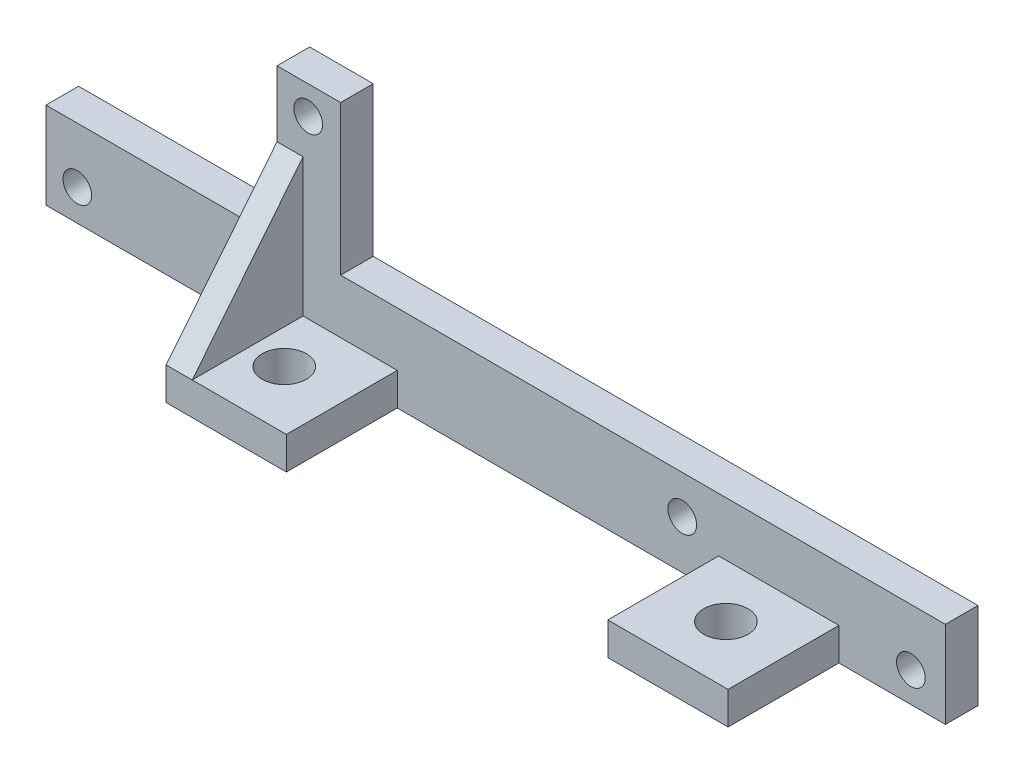
SolidWorks part; units mm, degrees
ref_plane "Front Plane" through (0, 0, 0) normal (0, 0, 1) x (1, 0, 0)
ref_plane "Top Plane" through (0, 0, 0) normal (0, 1, 0) x (1, 0, 0)
ref_plane "Right Plane" through (0, 0, 0) normal (1, 0, 0) x (0, 0, -1)
sketch "Sketch1" plane through (0, 0, 0) normal (0, 0, 1) x (1, 0, 0)
  line L1 (-43, 11.5) -> (43, 11.5)
  line L2 (-43, 11.5) -> (-43, -11.5)
  line L3 (-43, -11.5) -> (43, -11.5)
  line L4 (43, 11.5) -> (43, -11.5)
  point P0 (0, 0)
  dimension "D1" = 86
  dimension "D2" = 23
extrude "Boss-Extrude1" add sketch "Sketch1" against normal blind 3.175 contours L2 L1 L4 L3
ref_plane "Plane1" through (0, -11.5, 0) normal (0, -1, 0) x (-1, 0, 0)
sketch "Sketch3" plane through (0, -11.5, 0) normal (0, -1, 0) x (-1, 0, 0)
  line L0 (34.2, 0) -> (34.2, -10.795)
  line L1 (34.2, -10.795) -> (8.8, -10.795)
  line L2 (8.8, -10.795) -> (8.8, 0)
  line L3 (43, 0) -> (-43, 0) construction
  line L4 (34.2, 0) -> (8.8, 0)
  line L5 (0, 19.3889) -> (0, -14.044) construction
  line L6 (-34.2, 0) -> (-34.2, -10.795)
  line L7 (-34.2, -10.795) -> (-8.8, -10.795)
  line L8 (-8.8, -10.795) -> (-8.8, 0)
  line L9 (-34.2, 0) -> (-8.8, 0)
  line L10 (43, 3.175) -> (-43, 3.175) construction
  point P13 (21.5, 0)
  dimension "D2" = 13.97
  dimension "D3" = 21.5
extrude "Boss-Extrude2" add sketch "Sketch3" against normal blind 3.175
sketch "Sketch13" plane through (0, 11.5, 0) normal (0, 1, 0) x (1, 0, 0)
  line L0 (0, 3.175) -> (0, 0)
  line L1 (-43, 3.175) -> (43, 3.175) construction
ref_plane "Plane4" through (0, 0, 0) normal (1, 0, 0) x (0, 0, -1)
ref_plane "Plane6" through (0, 11.5, 0) normal (0, 1, 0) x (1, 0, 0)
sketch "Sketch18" plane through (0, 11.5, 0) normal (0, 1, 0) x (1, 0, 0)
  line L0 (-21.5, -10.795) -> (-21.5, 10.3861) construction
  line L1 (-8.8, -10.795) -> (-34.2, -10.795) construction
  line L2 (0, 8.5709) -> (0, -12.3789) construction
  circle A2 centre (-14.6263, -5.1774) radius 2.159
  circle A3 centre (28.3737, -5.1774) radius 2.159
extrude "Cut-Extrude2" cut sketch "Sketch18" against normal blind 127
sketch "Sketch19" plane through (0, 0, -3.175) normal (0, 0, -1) x (-1, 0, 0)
  circle A5 centre (-41.206, -8.579) radius 1.397
  circle A6 centre (-18.9429, -6.801) radius 1.397
  circle A7 centre (17.473, 8.7438) radius 1.397
  circle A8 centre (39.952, -8.452) radius 1.397
extrude "Cut-Extrude3" cut sketch "Sketch19" against normal through all
sketch "Sketch27" plane through (0, 0, -3.175) normal (0, 0, -1) x (-1, 0, 0)
  line L1 (-43, 11.5) -> (14.3155, 11.5)
  line L2 (-43, 11.5) -> (-43, -3.0562)
  line L3 (-43, -3.0562) -> (14.3155, -3.0562)
  line L4 (14.3155, 11.5) -> (14.3155, -3.0562)
  line L5 (43, 11.5) -> (20.5101, 11.5)
  line L6 (43, 11.5) -> (43, -3.0562)
  line L7 (43, -3.0562) -> (20.5101, -3.0562)
  line L8 (20.5101, 11.5) -> (20.5101, -3.0562)
  circle A0 centre (-18.9429, -6.801) radius 1.397 construction
  point P14 (-18.9429, -5.404)
  dimension "D1" = 2.3478
sketch "Sketch28" plane through (0, 0, -3.175) normal (0, 0, -1) x (-1, 0, 0)
  line L4 (-43, -11.5) -> (-43, -3.0562)
  line L5 (-43, -11.5) -> (-44.5635, -11.5)
  line L6 (-43, -3.0562) -> (-44.5635, -3.0562)
  line L7 (-44.5635, -11.5) -> (-44.5635, -3.0562)
  line L8 (-43, 11.5) -> (-43, -11.5) construction
  dimension "D1" = 8.4438
extrude "Boss-Extrude4" add sketch "Sketch28" against normal blind 3.175
extrude "Cut-Extrude5" cut sketch "Sketch27" against normal blind 3.175
sketch "Sketch29" plane through (0, 11.5, 0) normal (0, 1, 0) x (1, 0, 0)
  line L6 (8.8, 0) -> (22.4899, 0)
  line L7 (8.8, 0) -> (8.8, -10.795)
  line L8 (8.8, -10.795) -> (22.4899, -10.795)
  line L9 (22.4899, 0) -> (22.4899, -10.795)
  line L15 (-8.8, -10.795) -> (-34.2, -10.795) construction
  line L16 (-34.2, 0) -> (-20.5101, 0)
  line L17 (-34.2, 0) -> (-34.2, -10.795)
  line L18 (-34.2, -10.795) -> (-20.5101, -10.795)
  line L19 (-20.5101, 0) -> (-20.5101, -10.795)
  dimension "D1" = 13.6899
  dimension "D2" = 13.6899
extrude "Cut-Extrude6" cut sketch "Sketch29" against normal blind 50.8
ref_plane "Plane7" through (-20.5101, 0, 0) normal (-1, 0, 0) x (0, 0, 1)
sketch "Sketch30" plane through (-20.5101, 0, 0) normal (-1, 0, 0) x (0, 0, 1)
  line L0 (0, 5.0998) -> (10.795, -8.325)
  line L1 (0, 11.5) -> (0, -3.0562) construction
rib "Rib3" sketch "Sketch30" sketch "Sketch30" thickness 2.54 extrusion direction parallel to sketch draft on no parameters "D1"=2.54
